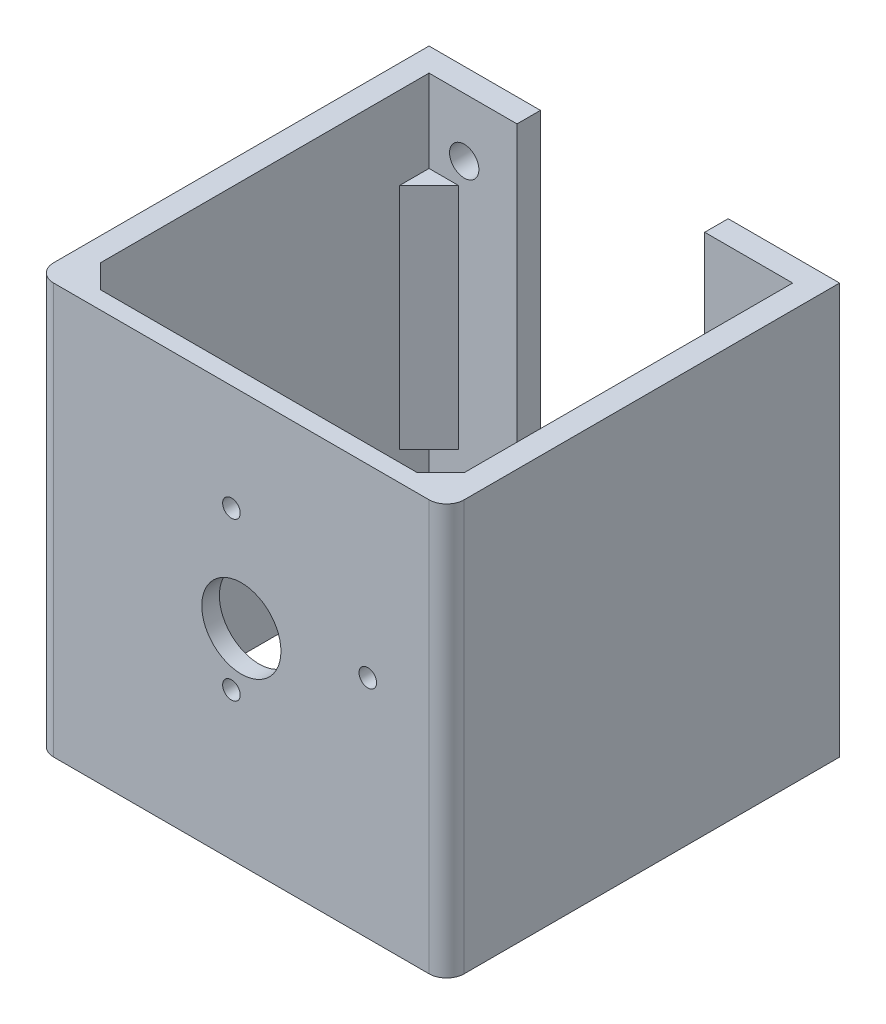
SolidWorks part; units mm, degrees
ref_plane "前视基准面" through (0, 0, 0) normal (0, 0, 1) x (1, 0, 0)
ref_plane "上视基准面" through (0, 0, 0) normal (0, 1, 0) x (1, 0, 0)
ref_plane "右视基准面" through (0, 0, 0) normal (1, 0, 0) x (0, 0, -1)
sketch "Sketch1" plane through (0, 0, 0) normal (0, 0, 1) x (1, 0, 0)
  line L1 (-44.6058, 34.082) -> (25.3942, 34.082)
  line L2 (-44.6058, 34.082) -> (-44.6058, -35.918)
  line L3 (-44.6058, -35.918) -> (25.3942, -35.918)
  line L4 (25.3942, 34.082) -> (25.3942, -35.918)
extrude "Boss-Extrude2" add sketch "Sketch1" along normal blind 3
sketch "Sketch2" plane through (0, 0, 3) normal (0, 0, 1) x (1, 0, 0)
  circle A5 centre (-9.6058, -0.918) radius 6.75
  circle A6 centre (-11.2936, 16.0054) radius 1.5
  circle A7 centre (11.9564, 2.582) radius 1.5
  circle A8 centre (-11.2936, -10.8414) radius 1.5
  point P14 (-3.5436, 2.582)
  dimension "D1" = 3
extrude "Cut-Extrude1" cut sketch "Sketch2" against normal blind 4
sketch "Sketch3" plane through (25.3942, 0, 0) normal (1, 0, 0) x (0, 0, -1)
  line L0 (0, 34.082) -> (64, 34.082)
  line L1 (64, 34.082) -> (64, -35.918)
  line L2 (64, -35.918) -> (0, -35.918)
  line L3 (0, -35.918) -> (0, 34.082)
extrude "Boss-Extrude3" add sketch "Sketch3" against normal blind 4
sketch "Sketch4" plane through (-44.6058, 0, 0) normal (-1, 0, 0) x (0, 0, 1)
  line L0 (0, 34.082) -> (-64, 34.082)
  line L1 (-64, 34.082) -> (0, 34.082) construction
  line L2 (-64, -35.918) -> (-64, 34.082) construction
  line L3 (-64, 34.082) -> (-64, -35.918)
  line L4 (-64, -35.918) -> (0, -35.918)
  line L5 (0, -35.918) -> (0, 34.082)
extrude "Boss-Extrude4" add sketch "Sketch4" against normal blind 4
sketch "Sketch5" plane through (0, 0, -64) normal (0, 0, -1) x (-1, 0, 0)
  line L0 (-21.3942, 34.082) -> (-6.3942, 34.082)
  line L1 (-21.3942, 34.082) -> (40.6058, 34.082) construction
  line L2 (-6.3942, 34.082) -> (-6.3942, -35.918)
  line L3 (40.6058, -35.918) -> (-21.3942, -35.918) construction
  line L4 (-6.3942, -35.918) -> (-21.3942, -35.918)
  line L5 (-21.3942, -35.918) -> (-21.3942, 34.082)
  line L6 (40.6058, 34.082) -> (25.6058, 34.082)
  line L7 (25.6058, 34.082) -> (25.6058, -35.918)
  line L8 (25.6058, -35.918) -> (40.6058, -35.918)
  line L9 (40.6058, -35.918) -> (40.6058, 34.082)
extrude "Boss-Extrude5" add sketch "Sketch5" against normal blind 4
sketch "Sketch6" plane through (0, 0, -64) normal (0, 0, -1) x (-1, 0, 0)
  circle A0 centre (-15.3942, 24.082) radius 2.5
  circle A1 centre (-15.3942, -25.918) radius 2.5
  circle A2 centre (34.6058, 24.082) radius 2.5
  circle A3 centre (34.6058, -25.918) radius 2.5
extrude "Cut-Extrude2" cut sketch "Sketch6" against normal blind 4
sketch "Sketch7" plane through (0, 34.082, 0) normal (0, 1, 0) x (1, 0, 0)
  line L3 (-40.6058, 0) -> (-40.6058, 60) construction
  line L8 (21.3942, 60) -> (21.3942, 0) construction
  line L10 (-40.6058, 0) -> (-40.6058, 4)
  line L11 (-40.6058, 4) -> (-36.6058, 0)
  line L12 (21.3942, 0) -> (-40.6058, 0) construction
  line L13 (-36.6058, 0) -> (-40.6058, 0)
  line L14 (21.3942, 0) -> (21.3942, 4)
  line L15 (21.3942, 4) -> (17.3942, 0)
  line L16 (17.3942, 0) -> (21.3942, 0)
extrude "Boss-Extrude6" add sketch "Sketch7" against normal blind 70
sketch "Sketch8" plane through (0, 0, 0) normal (0, 1, 0) x (1, 0, 0)
  line L0 (-40.6058, 60) -> (-35.6058, 60)
  line L1 (-40.6058, 60) -> (-25.6058, 60) construction
  line L2 (-35.6058, 60) -> (-40.6058, 55)
  line L3 (-40.6058, 4) -> (-40.6058, 60) construction
  line L4 (-40.6058, 55) -> (-40.6058, 60)
  line L5 (21.3942, 60) -> (16.3942, 60)
  line L6 (6.3942, 60) -> (21.3942, 60) construction
  line L7 (16.3942, 60) -> (21.3942, 55)
  line L8 (21.3942, 60) -> (21.3942, 4) construction
  line L9 (21.3942, 55) -> (21.3942, 60)
extrude "Boss-Extrude7" add sketch "Sketch8" along normal blind 20 and the other way blind 19
fillet "Fillet1" radius 3 2 edges at (25.3942, -0.918, 3) (-44.6058, -0.918, 3)
